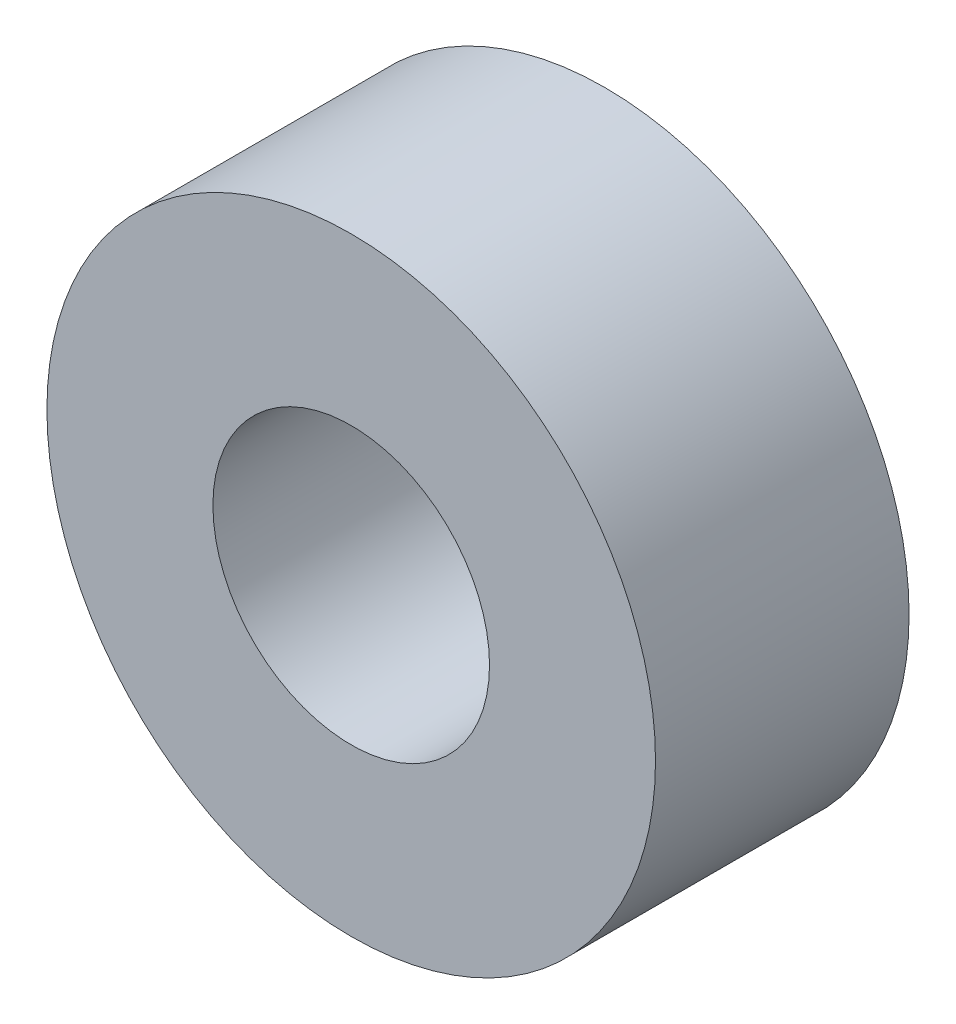
SolidWorks part; units mm, degrees
ref_plane "Front Plane" through (0, 0, 0) normal (0, 0, 1) x (1, 0, 0)
ref_plane "Top Plane" through (0, 0, 0) normal (0, 1, 0) x (1, 0, 0)
ref_plane "Right Plane" through (0, 0, 0) normal (1, 0, 0) x (0, 0, -1)
sketch "Sketch1" plane through (0, 0, 0) normal (0, 0, 1) x (1, 0, 0)
  circle A0 centre (0, 0) radius 1.5
  circle A1 centre (0, 0) radius 3.3
  dimension "D1" = 3
  dimension "D2" = 6.6
extrude "Boss-Extrude1" add sketch "Sketch1" along normal mid plane 2.75
